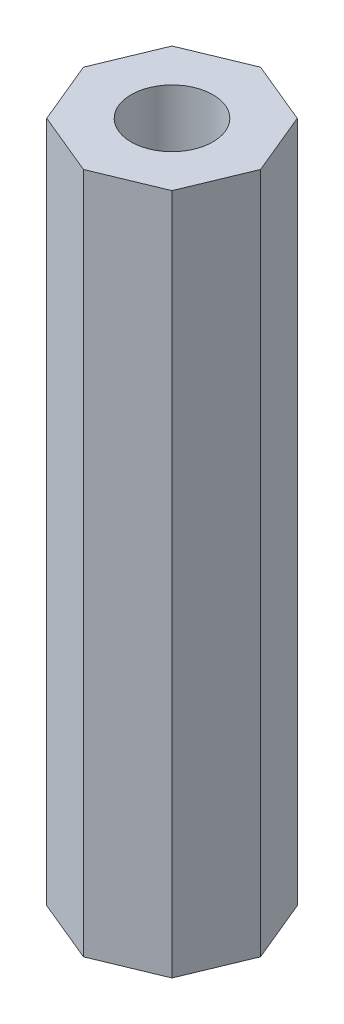
SolidWorks part; units mm, degrees
ref_plane "Front" through (0, 0, 0) normal (0, 0, 1) x (1, 0, 0)
ref_plane "Top" through (0, 0, 0) normal (0, 1, 0) x (1, 0, 0)
ref_plane "Right" through (0, 0, 0) normal (1, 0, 0) x (0, 0, -1)
sketch "Sketch1" plane through (0, 0, 0) normal (0, 1, 0) x (1, 0, 0)
  line L1 (1.6236, 0) -> (1.1481, 1.1481)
  line L2 (1.1481, 1.1481) -> (0, 1.6236)
  line L3 (0, 1.6236) -> (-1.1481, 1.1481)
  line L4 (-1.1481, 1.1481) -> (-1.6236, 0)
  line L5 (-1.6236, 0) -> (-1.1481, -1.1481)
  line L6 (-1.1481, -1.1481) -> (0, -1.6236)
  line L7 (0, -1.6236) -> (1.1481, -1.1481)
  line L8 (1.1481, -1.1481) -> (1.6236, 0)
  circle A0 centre (0, 0) radius 1.5 construction
  circle A1 centre (0, 0) radius 0.75
extrude "Boss-Extrude1" add sketch "Sketch1" along normal blind 12.5
